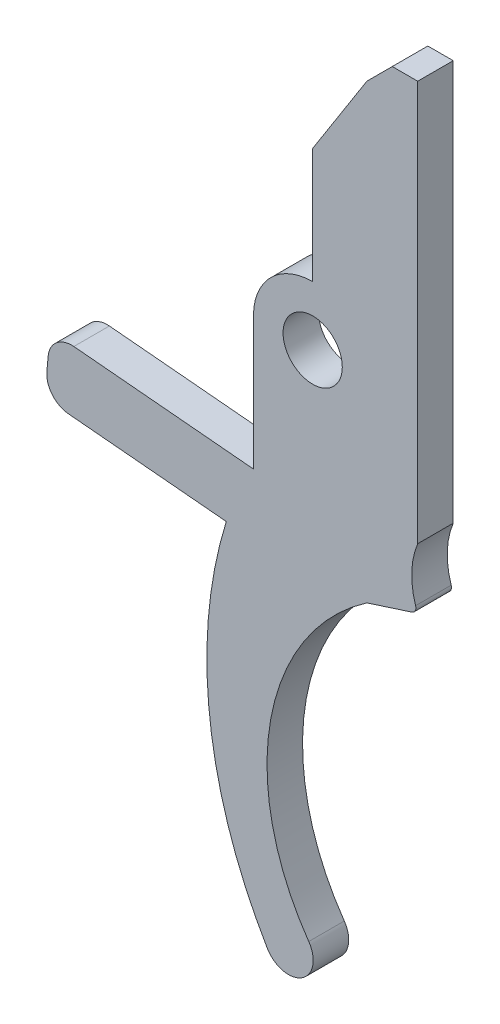
SolidWorks part; units mm, degrees
ref_plane "정면" through (0, 0, 0) normal (0, 0, 1) x (1, 0, 0)
ref_plane "윗면" through (0, 0, 0) normal (0, 1, 0) x (1, 0, 0)
ref_plane "우측면" through (0, 0, 0) normal (1, 0, 0) x (0, 0, -1)
sketch "스케치1" plane through (0, 0, 0) normal (0, 0, 1) x (1, 0, 0)
  line L0 (6.7207, 24.0891) -> (8.8664, 24.0891)
  line L1 (6.7207, 24.0891) -> (4.575, 21.9434)
  line L2 (8.8664, 24.0891) -> (8.8664, -9.7282)
  line L3 (-5, 0) -> (-5, -11.2023)
  line L4 (-5, -11.2023) -> (-20.1625, -9.8229)
  line L5 (-22.3354, -11.6335) -> (-22.4417, -12.8015)
  line L6 (-20.6311, -14.9744) -> (-7.2931, -16.1878)
  line L10 (2.2148, 21.9434) -> (17.8049, 21.9434) construction
  line L11 (4.575, 21.9434) -> (0, 14.7432)
  line L12 (0, 14.7432) -> (0, 5)
  line L14 (8.3701, -14.9782) -> (4.575, -16.201)
  circle A0 centre (0, 0) radius 2.5
  circle A1 centre (0, 0) radius 5
  arc A2 (4.575, -16.201) -> (-0.331, -43.4123) centre (15.613, -32.2389) ccw
  arc A3 (-7.2931, -16.1878) -> (-3.8242, -45.6665) centre (27.6461, -27.0197) ccw
  arc A4 (-3.8242, -45.6665) -> (-0.331, -43.4123) centre (-2.0345, -44.6061) ccw
  arc A5 (-22.4417, -12.8015) -> (-20.6311, -14.9744) centre (-20.4499, -12.9827) ccw
  arc A6 (-20.1625, -9.8229) -> (-22.3354, -11.6335) centre (-20.3437, -11.8147) ccw
  arc A7 (8.8664, -9.7282) -> (8.6919, -14.3466) centre (15.0215, -12.2733) ccw
  arc A8 (8.6919, -14.3466) -> (8.3701, -14.9782) centre (8.2168, -14.5023) cw
  dimension "D1" = 5
  dimension "D2" = 10
  dimension "D4" = 2
  dimension "D5" = 0.5
  dimension "D3" = 45
extrude "보스-돌출1" add sketch "스케치1" along normal blind 3
